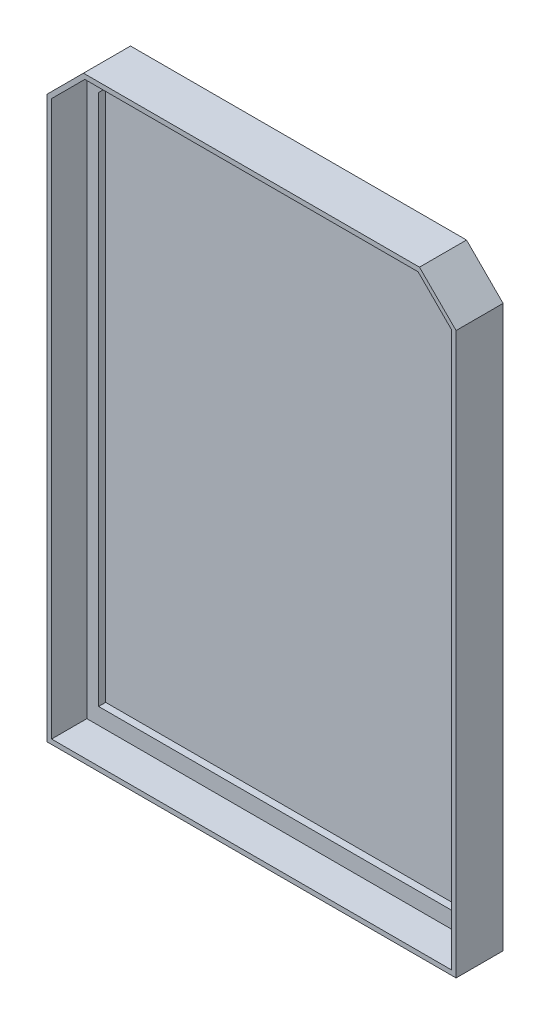
SolidWorks part; units mm, degrees
ref_plane "Front Plane" through (0, 0, 0) normal (1, 0, 0) x (0, 1, 0)
ref_plane "Top Plane" through (0, 0, 0) normal (0, 0, 1) x (0, 1, 0)
ref_plane "Right Plane" through (0, 0, 0) normal (0, 1, 0) x (-1, 0, 0)
sketch "Sketch1" plane through (0, 0, 0) normal (0, 0, 1) x (0, 1, 0)
  line L0 (54.0503, 40) -> (59, 35.0503)
  line L1 (-62.5, -42.5) -> (62.5, -42.5) construction
  line L2 (-62.5, -42.5) -> (-62.5, 42.5)
  line L3 (-62.5, 42.5) -> (62.5, 42.5) construction
  line L4 (62.5, -42.5) -> (62.5, 42.5) construction
  line L5 (-62.5, -42.5) -> (62.5, 42.5) construction
  line L6 (-62.5, 42.5) -> (62.5, -42.5) construction
  line L7 (-59, -40) -> (59, -40) construction
  line L8 (-59, -40) -> (-59, 40)
  line L9 (-59, 40) -> (59, 40) construction
  line L10 (59, -40) -> (59, 40) construction
  line L11 (-59, -40) -> (59, 40) construction
  line L12 (-59, 40) -> (59, -40) construction
  line L13 (-63.5, -43.5) -> (63.5, -43.5) construction
  line L14 (-63.5, -43.5) -> (-63.5, 43.5)
  line L15 (-63.5, 43.5) -> (63.5, 43.5) construction
  line L16 (63.5, -43.5) -> (63.5, 43.5) construction
  line L17 (-63.5, -43.5) -> (63.5, 43.5) construction
  line L18 (-63.5, 43.5) -> (63.5, -43.5) construction
  line L19 (-59, 40) -> (54.0503, 40)
  line L20 (59, 35.0503) -> (59, -40) construction
  line L21 (59, -35.0503) -> (54.0503, -40)
  line L22 (59, -35.0503) -> (59, 35.0503)
  line L23 (54.0503, -40) -> (-59, -40)
  line L24 (55.4289, 42.5) -> (62.5, 35.4289)
  line L25 (62.5, -35.4289) -> (55.4289, -42.5)
  line L26 (55.4289, -42.5) -> (-62.5, -42.5)
  line L27 (62.5, -35.4289) -> (62.5, 35.4289)
  line L28 (55.4289, 42.5) -> (-62.5, 42.5)
  line L29 (55.7218, 43.5) -> (63.5, 35.7218)
  line L30 (63.5, -35.7218) -> (55.7218, -43.5)
  line L31 (55.7218, -43.5) -> (-63.5, -43.5)
  line L32 (63.5, -35.7218) -> (63.5, 35.7218)
  line L33 (55.7218, 43.5) -> (-63.5, 43.5)
  point P0 (0, 0)
  point P5 (0, 0)
  point P11 (0, 0)
  dimension "D1" = 85
  dimension "D2" = 125
  dimension "D3" = 118
  dimension "D4" = 80
  dimension "D5" = 87
  dimension "D6" = 127
  dimension "D7" = 7
  dimension "D8" = 45
  dimension "D9" = 7
  dimension "D10" = 45
  dimension "D11" = 10
  dimension "D12" = 10
  dimension "D13" = 11
  dimension "D14" = 11
extrude "Boss-Extrude1" add sketch "Sketch1" along normal blind 1.5 contours L1 L4 L3 L2 L10 L7 L8 L9
sketch "Sketch2" plane through (0, 0, 0) normal (0, 0, 1) x (0, 1, 0)
  line L4 (55.7218, 43.5) -> (-63.5, 43.5)
  line L5 (55.7218, 43.5) -> (-63.5, 43.5)
  line L6 (63.5, 35.7218) -> (55.7218, 43.5)
  line L7 (-63.5, 43.5) -> (-63.5, -43.5)
  line L11 (-63.5, 43.5) -> (-63.5, -43.5)
  line L12 (54.0503, 40) -> (-59, 40)
  line L13 (54.0503, 40) -> (-59, 40)
  line L14 (59, 35.0503) -> (54.0503, 40)
  line L15 (-59, 40) -> (-59, -40)
  line L19 (-59, 40) -> (-59, -40) construction
  line L20 (55.4289, 42.5) -> (-62.5, 42.5)
  line L21 (55.4289, 42.5) -> (-62.5, 42.5)
  line L22 (62.5, 35.4289) -> (55.4289, 42.5)
  line L23 (-62.5, 42.5) -> (-62.5, -42.5)
  line L27 (-62.5, 42.5) -> (-62.5, -42.5)
  line L30 (59, 35.0503) -> (54.0503, 40)
  line L31 (59, -35.0503) -> (59, 35.0503)
  line L32 (59, -35.0503) -> (59, 35.0503)
  line L33 (54.0503, -40) -> (59, -35.0503)
  line L34 (54.0503, -40) -> (59, -35.0503)
  line L35 (-59, -40) -> (54.0503, -40)
  line L36 (-59, -40) -> (54.0503, -40)
  line L37 (62.5, 35.4289) -> (55.4289, 42.5)
  line L38 (62.5, -35.4289) -> (62.5, 35.4289)
  line L39 (62.5, -35.4289) -> (62.5, 35.4289)
  line L40 (55.4289, -42.5) -> (62.5, -35.4289)
  line L41 (55.4289, -42.5) -> (62.5, -35.4289)
  line L42 (-62.5, -42.5) -> (55.4289, -42.5)
  line L43 (-62.5, -42.5) -> (55.4289, -42.5)
  line L44 (63.5, 35.7218) -> (55.7218, 43.5)
  line L45 (63.5, -35.7218) -> (63.5, 35.7218)
  line L46 (63.5, -35.7218) -> (63.5, 35.7218)
  line L47 (55.7218, -43.5) -> (63.5, -35.7218)
  line L48 (55.7218, -43.5) -> (63.5, -35.7218)
  line L49 (-63.5, -43.5) -> (55.7218, -43.5)
  line L50 (-63.5, -43.5) -> (55.7218, -43.5)
  dimension "D1" = 0
  dimension "D2" = 0
  dimension "D3" = 0
extrude "Boss-Extrude2" add sketch "Sketch2" along normal blind 9 contours L11 L50 L48 L46 L44 L5 L43 L27 L21 L37 L39 L41
sketch "Sketch3" plane through (0, 0, 0) normal (0, 0, 1) x (0, 1, 0)
  line L4 (55.7218, 43.5) -> (-63.5, 43.5)
  line L5 (55.7218, 43.5) -> (-63.5, 43.5)
  line L6 (63.5, 35.7218) -> (55.7218, 43.5)
  line L7 (-63.5, 43.5) -> (-63.5, -43.5)
  line L11 (-63.5, 43.5) -> (-63.5, -43.5)
  line L12 (54.0503, 40) -> (-59, 40)
  line L13 (54.0503, 40) -> (-59, 40)
  line L14 (59, 35.0503) -> (54.0503, 40)
  line L15 (-59, 40) -> (-59, -40)
  line L19 (-59, 40) -> (-59, -40) construction
  line L20 (55.4289, 42.5) -> (-62.5, 42.5)
  line L21 (55.4289, 42.5) -> (-62.5, 42.5)
  line L22 (62.5, 35.4289) -> (55.4289, 42.5)
  line L23 (-62.5, 42.5) -> (-62.5, -42.5)
  line L27 (-62.5, 42.5) -> (-62.5, -42.5) construction
  line L30 (59, 35.0503) -> (54.0503, 40)
  line L31 (59, -35.0503) -> (59, 35.0503)
  line L32 (59, -35.0503) -> (59, 35.0503)
  line L33 (54.0503, -40) -> (59, -35.0503)
  line L34 (54.0503, -40) -> (59, -35.0503)
  line L35 (-59, -40) -> (54.0503, -40)
  line L36 (-59, -40) -> (54.0503, -40)
  line L37 (62.5, 35.4289) -> (55.4289, 42.5)
  line L38 (62.5, -35.4289) -> (62.5, 35.4289)
  line L39 (62.5, -35.4289) -> (62.5, 35.4289)
  line L40 (55.4289, -42.5) -> (62.5, -35.4289)
  line L41 (55.4289, -42.5) -> (62.5, -35.4289)
  line L42 (-62.5, -42.5) -> (55.4289, -42.5)
  line L43 (-62.5, -42.5) -> (55.4289, -42.5)
  line L44 (63.5, 35.7218) -> (55.7218, 43.5)
  line L45 (63.5, -35.7218) -> (63.5, 35.7218)
  line L46 (63.5, -35.7218) -> (63.5, 35.7218)
  line L47 (55.7218, -43.5) -> (63.5, -35.7218)
  line L48 (55.7218, -43.5) -> (63.5, -35.7218)
  line L49 (-63.5, -43.5) -> (55.7218, -43.5)
  line L50 (-63.5, -43.5) -> (55.7218, -43.5)
  dimension "D1" = 0
  dimension "D2" = 0
  dimension "D3" = 0
extrude "Boss-Extrude3" add sketch "Sketch3" against normal blind 1
sketch "Sketch4" plane through (0, 0, -1) normal (0, 0, -1) x (1, 0, 0)
  circle A0 centre (0, 0) radius 5
  circle A1 centre (0, 0) radius 4
  dimension "D1" = 8
  dimension "D2" = 10
extrude "Boss-Extrude4" add sketch "Sketch4" along normal blind 10
fillet "Fillet1" radius 5 1 edges at (5, 0, -1)
